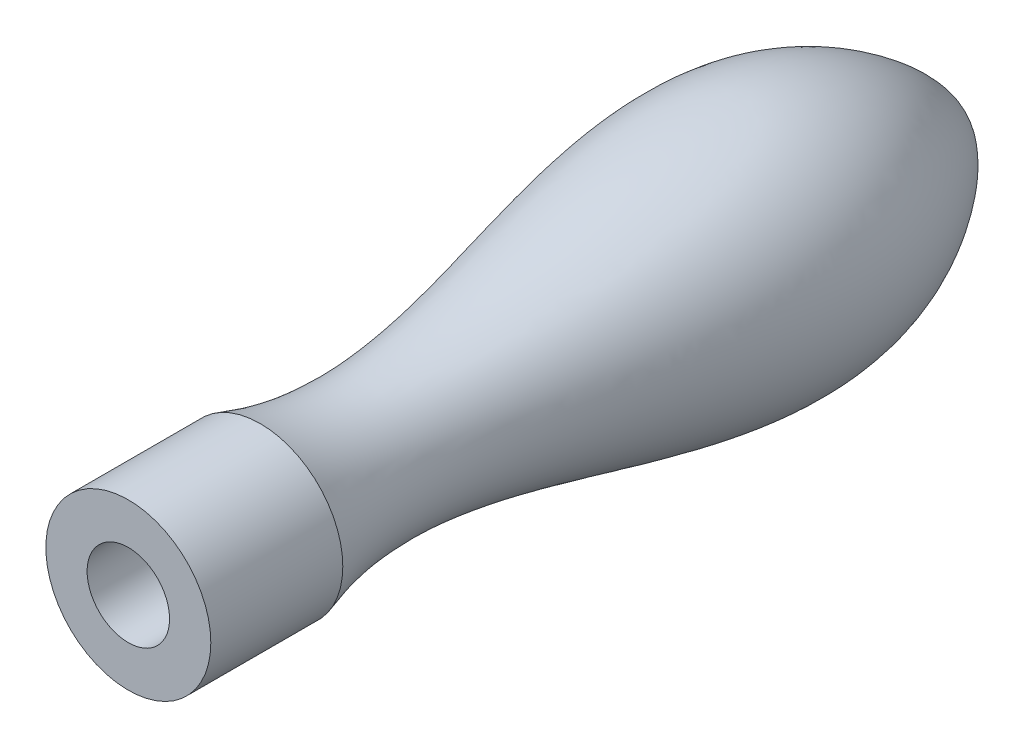
SolidWorks part; units mm, degrees
ref_plane "Спереди" through (0, 0, 0) normal (0, 0, 1) x (1, 0, 0)
ref_plane "Сверху" through (0, 0, 0) normal (0, 1, 0) x (1, 0, 0)
ref_plane "Справа" through (0, 0, 0) normal (1, 0, 0) x (0, 0, -1)
other "Configuration Table"
sketch "Эскиз1" plane through (0, 0, 0) normal (1, 0, 0) x (0, 0, -1)
  line L0 (0, 0) -> (100, 0) construction
  line L1 (0, 0) -> (0, 10)
  line L2 (0, 10) -> (6, 10)
  line L4 (6, 10) -> (16, 10)
  line L5 (0, 0) -> (100, 0)
  spline S0 degree 3 poles (16, 10) (34.1239, 3.7934) (59.3547, 17.8807) (89.0909, 13.9735) (100, 3.7147) (100, 0) knots 0 0 0 0 0.303771 0.428947 0.5 0.5 0.5 0.5
  dimension "D1" = 30
  dimension "D2" = 70
  dimension "D3" = 100
  dimension "D4" = 10
  dimension "D5" = 6
  dimension "D6" = 92
  dimension "D7" = 8
  dimension "D8" = 15
revolve "Повернуть1" add sketch "Эскиз1" angle 360 about L0
sketch "Эскиз2" plane through (0, 0, 0) normal (1, 0, 0) x (0, 0, -1)
  line L0 (0, 0) -> (0, 5)
  line L1 (0, 10) -> (0, -10) construction
  line L2 (0, 5) -> (80, 5)
  line L3 (80, 5) -> (82.8868, 0)
  line L4 (0, 0) -> (82.8868, 0) construction
  line L5 (0, 0) -> (82.8868, 0)
  dimension "D1" = 120
  dimension "D2" = 80
  dimension "D3" = 82.8868
revolve "Вырез-Повернуть1" cut sketch "Эскиз2" angle 360 about L4
sketch "Эскиз3" plane through (0, 0, 0) normal (1, 0, 0) x (0, 0, -1)
  line L0 (0, 0) -> (16, 0) construction
  line L1 (0, 5) -> (0, -5) construction
  line L2 (14.8, 0) -> (17.2, 0)
  line L4 (14.8, 6) -> (14.8, 0)
  line L5 (17.2, 6) -> (17.2, 0)
  arc A1 (17.2, 6) -> (14.8, 6) centre (16, 6) ccw
  dimension "D1" = 2.4
  dimension "D2" = 16
  dimension "D3" = 6
revolve "Вырез-Повернуть2" cut sketch "Эскиз3" angle 360 about L0
sketch "Эскиз5" plane through (0, 0, 0) normal (1, 0, 0) x (0, 0, -1)
  line L0 (17.2, 0) -> (14.8, 0) construction
  line L1 (17.2, 6) -> (17.2, -6) construction
  circle A1 centre (16, 5.5) radius 1.2
  dimension "D2" = 2.4
  dimension "D1" = 16
  dimension "D3" = 5.5
revolve "Повернуть2" add sketch "Эскиз5" angle 360 about L0
ref_plane "Плоскость1" through (0, 0, -16) normal (0, 0, 1) x (1, 0, 0)
sketch "Эскиз6" plane through (0, 0, -16) normal (0, 0, 1) x (1, 0, 0)
  line L1 (-2.0894, 3.619) -> (-3.4394, 5.9573)
  line L2 (-2.0894, 3.619) -> (-3.4394, 5.9573)
  line L3 (-4.0364, 1.0816) -> (-6.6445, 1.7804)
  arc A0 (-2.0894, 3.619) -> (-4.0364, 1.0816) centre (0, 0) ccw
  arc A1 (-3.4394, 5.9573) -> (-6.6445, 1.7804) centre (0, 0) ccw
  dimension "D3" = 2.0894
  dimension "D1" = 4.1788
  dimension "D2" = 6.8789
  dimension "D4" = 4.0364
extrude "Вырез-Вытянуть1" cut sketch "Эскиз6" against normal mid plane 2.4 contours L1 A1 L3 A0
